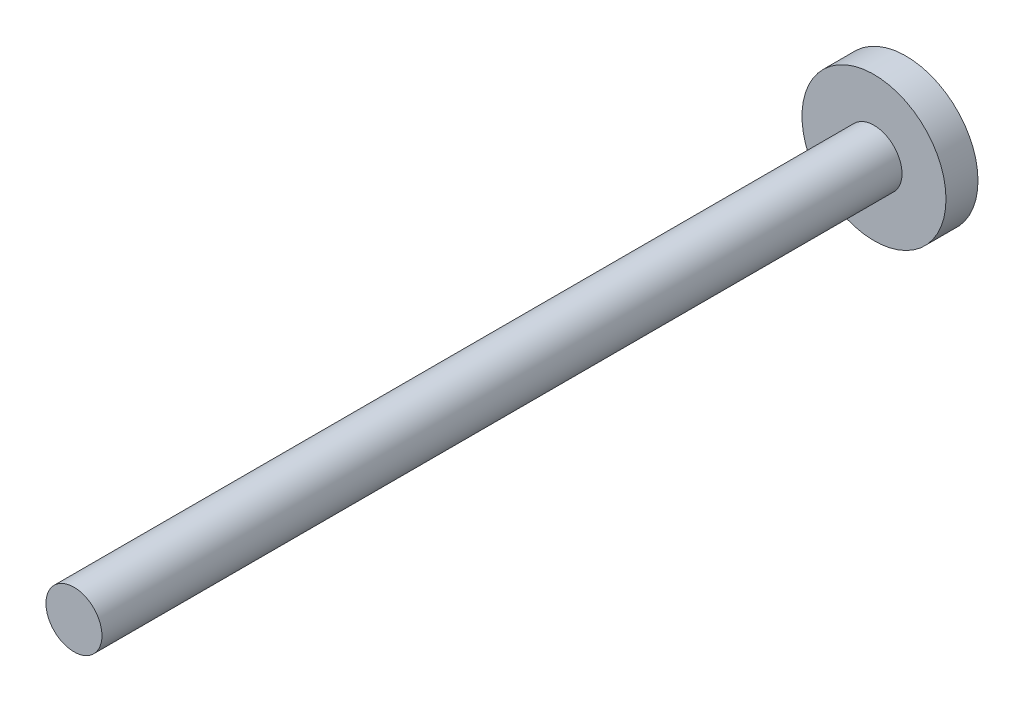
SolidWorks part; units mm, degrees
ref_plane "Front Plane" through (0, 0, 0) normal (0, 0, 1) x (1, 0, 0)
ref_plane "Top Plane" through (0, 0, 0) normal (0, 1, 0) x (1, 0, 0)
ref_plane "Right Plane" through (0, 0, 0) normal (1, 0, 0) x (0, 0, -1)
sketch "Sketch1" plane through (0, 0, 0) normal (0, 0, 1) x (1, 0, 0)
  circle A0 centre (0, 0) radius 4.5
  dimension "D1" = 9
extrude "Boss-Extrude1" add sketch "Sketch1" along normal blind 2
sketch "Sketch2" plane through (0, 0, 2) normal (0, 0, 1) x (1, 0, 0)
  circle A0 centre (0, 0) radius 1.75
  dimension "D1" = 3.5
extrude "Boss-Extrude2" add sketch "Sketch2" along normal blind 50
